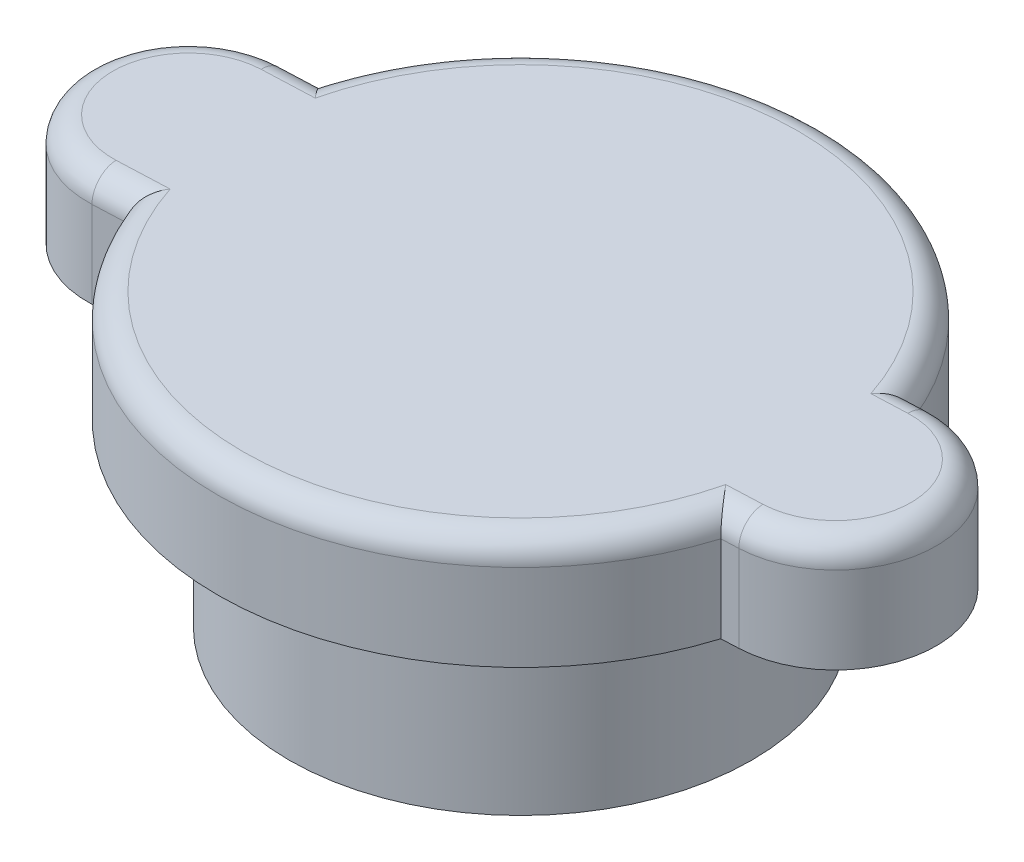
SolidWorks part; units mm, degrees
ref_plane "Front Plane" through (0, 0, 0) normal (0, 0, 1) x (1, 0, 0)
ref_plane "Top Plane" through (0, 0, 0) normal (0, 1, 0) x (1, 0, 0)
ref_plane "Right Plane" through (0, 0, 0) normal (1, 0, 0) x (0, 0, -1)
sketch "Sketch1" plane through (0, 0, 0) normal (0, 1, 0) x (1, 0, 0)
  line L0 (0, 0) -> (-25.3787, -1.0412)
  circle A0 centre (0, 0) radius 25.4
  circle A1 centre (0, 0) radius 23.4
  point P4 (-14.9799, -20.5125)
  dimension "D1" = 50.8
  dimension "D2" = 46.8
sketch "Sketch11" plane through (0, 0, 0) normal (0, 1, 0) x (1, 0, 0)
  circle A0 centre (0, 0) radius 18.415
  dimension "D1" = 36.83
extrude "neck" add sketch "Sketch11" along normal blind 14.224
sketch "Sketch12" plane through (0, 14.224, 0) normal (0, 1, 0) x (1, 0, 0)
  line L0 (-25.3787, -1.0412) -> (24.0782, 0.9878) construction
  line L1 (-25.7077, 6.9784) -> (23.7492, 9.0074)
  line L2 (-25.0496, -9.0608) -> (24.4073, -7.0318)
  circle A0 centre (0, 0) radius 24.0985
  arc A1 (-25.7077, 6.9784) -> (-25.0496, -9.0608) centre (-25.3787, -1.0412) ccw
  arc A2 (24.4073, -7.0318) -> (23.7492, 9.0074) centre (24.0782, 0.9878) ccw
  circle A3 centre (0, 0) radius 25.4 construction
  point P6 (-0.6502, -0.0267)
extrude "lid" add sketch "Sketch12" along normal blind 8.89 contours A0 | L2 A2 L1 A1
fillet "Fillet3" radius 2
equation "\"can_diameter\"= 2in"
equation "\"D1@can\" = \"can_thickness\""
equation "\"inlet_diameter\"=9.525"
